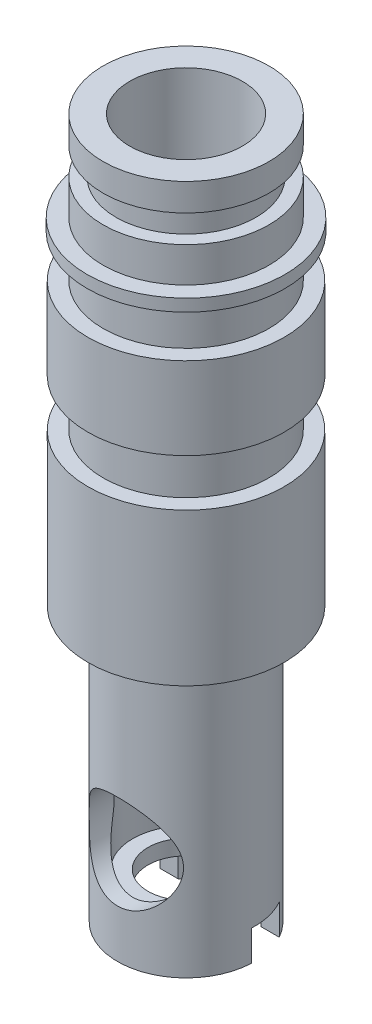
SolidWorks part; units mm, degrees
material "PW30:30:Sc:0:"
ref_plane "Plane1" through (0, 0, 0) normal (0, 0, 1) x (1, 0, 0)
ref_plane "Plane2" through (0, 0, 0) normal (0, 1, 0) x (1, 0, 0)
ref_plane "Plane3" through (0, 0, 0) normal (1, 0, 0) x (0, 0, -1)
sketch "Sketch2" plane through (0, 0, 0) normal (0, 0, 1) x (1, 0, 0)
  line L0 (0, 0) -> (0, -66.7498) construction
  line L1 (0, 0) -> (6.9215, 0)
  line L2 (6.9215, 0) -> (6.9215, -12.065)
  line L3 (6.9215, -12.065) -> (8.1915, -12.065)
  line L4 (8.1915, -12.065) -> (8.1915, -18.923)
  line L5 (8.1915, -18.923) -> (6.9215, -18.923)
  line L6 (6.9215, -18.923) -> (6.9215, -22.86)
  line L7 (6.9215, -22.86) -> (8.1915, -22.86)
  line L8 (8.1915, -22.86) -> (8.1915, -35.56)
  line L9 (8.1915, -35.56) -> (5.715, -35.56)
  line L10 (5.715, -35.56) -> (5.715, -58.42)
  line L11 (5.715, -58.42) -> (0, -58.42)
  line L12 (0, -58.42) -> (0, 0)
  dimension "D1" = 6.9215
  dimension "D2" = 8.1915
  dimension "D3" = 5.715
  dimension "D4" = 12.065
  dimension "D5" = 6.858
  dimension "D6" = 12.7
  dimension "D7" = 22.86
  dimension "D8" = 58.42
revolve "Main Shaft" add sketch "Sketch2" angle 360 about L0
sketch "Sketch3" plane through (0, 0, 0) normal (0, 0, 1) x (1, 0, 0)
  line L0 (0, 0) -> (0, -21.1506) construction
  line L1 (6.9215, -2.286) -> (5.842, -2.286)
  line L2 (6.9215, -2.286) -> (6.9215, -4.572)
  line L3 (5.842, -4.572) -> (6.9215, -4.572)
  line L4 (5.842, -4.572) -> (5.842, -2.286)
  point P7 (6.9215, 0)
  dimension "D1" = 2.286
  dimension "D2" = 2.286
  dimension "D3" = 5.842
revolve "Top Groove" cut sketch "Sketch3" angle 360 about L0
sketch "Sketch4" plane through (0, 0, 0) normal (0, 0, 1) x (1, 0, 0)
  line L0 (0, 0) -> (0, -11.861) construction
  line L1 (6.9215, -7.493) -> (8.255, -7.493)
  line L2 (6.9215, -7.493) -> (6.9215, -8.509)
  line L3 (8.255, -8.509) -> (6.9215, -8.509)
  line L4 (8.255, -8.509) -> (8.255, -7.493)
  line L5 (8.1915, -12.065) -> (-8.1915, -12.065) construction
  point P7 (6.9215, 0)
  dimension "D1" = 1.016
  dimension "D2" = 8.255
  dimension "D3" = 3.556
revolve "Upper Flange" add sketch "Sketch4" angle 360 about L0
sketch "Sketch5" plane through (0, 0, 0) normal (0, 0, 1) x (1, 0, 0)
  line L0 (0, 0) -> (0, -60.363) construction
  line L1 (0, 0) -> (4.699, 0)
  line L2 (4.699, 0) -> (4.699, -23.3593)
  line L3 (4.699, -23.3593) -> (4.445, -23.3593)
  line L4 (4.445, -23.3593) -> (4.445, -58.42)
  line L5 (4.445, -58.42) -> (0, -58.42)
  line L6 (0, -58.42) -> (0, 0)
  line L7 (5.715, -58.42) -> (-5.715, -58.42) construction
  line L8 (8.1915, -22.86) -> (-8.1915, -22.86) construction
  dimension "D1" = 4.445
  dimension "D2" = 4.699
  dimension "D3" = 0.4993
revolve "ID" cut sketch "Sketch5" angle 360 about L0
sketch "Sketch6" plane through (0, 0, 0) normal (0, 0, 1) x (1, 0, 0)
  line L0 (0, -50) -> (0, 50) construction
  line L1 (50, 0) -> (-50, 0) construction
  circle A0 centre (0, -50.4698) radius 3.937
  dimension "D1" = 7.874
  dimension "D2" = 50.4698
extrude "Air Out 2 Mouthpiece" cut sketch "Sketch6" along normal through all
sketch "Sketch7" plane through (0, 0, 0) normal (0, 0, 1) x (1, 0, 0)
  line L0 (50, 0) -> (-50, 0) construction
  line L1 (0, -50) -> (0, 50) construction
  circle A0 centre (0, -15.3416) radius 2.3495
  dimension "D1" = 4.699
  dimension "D2" = 15.3416
extrude "Air Out 2 BC" cut sketch "Sketch7" against normal through all
sketch "Sketch8" plane through (0, 0, 0) normal (0, 0, 1) x (1, 0, 0)
  line L0 (0, -50) -> (0, 50) construction
  line L1 (5.715, -58.42) -> (-5.715, -58.42) construction
  circle A0 centre (0, -49.53) radius 1.27
  dimension "D2" = 2.54
  dimension "D1" = 8.89
extrude "Vent" cut sketch "Sketch8" against normal through all
sketch "Sketch9" plane through (0, 0, 0) normal (1, 0, 0) x (0, 0, -1)
  line L0 (2.794, -58.42) -> (-0.254, -58.42)
  line L1 (2.794, -58.42) -> (2.794, -55.88)
  line L2 (-0.254, -55.88) -> (2.794, -55.88)
  line L3 (-0.254, -55.88) -> (-0.254, -58.42)
  line L4 (0, 50) -> (0, -50) construction
  line L5 (-5.715, -58.42) -> (5.715, -58.42) construction
  point P4 (1.27, -55.88)
  dimension "D1" = 1.27
  dimension "D2" = 3.048
  dimension "D3" = 2.54
extrude "Slot for Demand Lever" cut sketch "Sketch9" against normal through all and the other way through all
chamfer "Chamfer1" [suppressed] distance 0.254 angle 45
chamfer "Chamfer2" [suppressed] distance 0.127 angle 45
sketch "Sketch10" plane through (0, -35.56, 0) normal (0, -1, 0) x (1, 0, 0)
  line L0 (-8.1915, -5.715) -> (8.1915, -5.715)
  line L1 (-8.1915, -5.715) -> (-8.1915, -8.1915)
  line L2 (8.1915, -8.1915) -> (-8.1915, -8.1915)
  line L3 (8.1915, -8.1915) -> (8.1915, -5.715)
  circle A0 centre (0, 0) radius 5.715 construction
  circle A2 centre (0, 0) radius 8.1915 construction
extrude "Clocking cut" cut sketch "Sketch10" against normal blind 2.54
fillet "Fillet1" [suppressed] radius 0.254
chamfer "Chamfer3" [suppressed] distance 0.254 angle 45
sketch "Sketch11" plane through (0, -55.88, 0) normal (0, -1, 0) x (1, 0, 0)
  circle A0 centre (0, 0) radius 4.445
  circle A1 centre (0, 0) radius 4.445 construction
  circle A2 centre (0, 0) radius 3.175
  dimension "D1" = 6.35
extrude "Spring Rest" add sketch "Sketch11" against normal blind 1.27
sketch "Sketch12" plane through (0, 0, 0) normal (1, 0, 0) x (0, 0, -1)
  line L0 (-24.6337, 8.7951) -> (21.4175, 8.7951)
  line L1 (-24.6337, 8.7951) -> (-24.6337, -65.6744)
  line L2 (21.4175, -65.6744) -> (-24.6337, -65.6744)
  line L3 (21.4175, -65.6744) -> (21.4175, 8.7951)
extrude "CutAway" [suppressed] cut sketch "Sketch12" against normal through all
